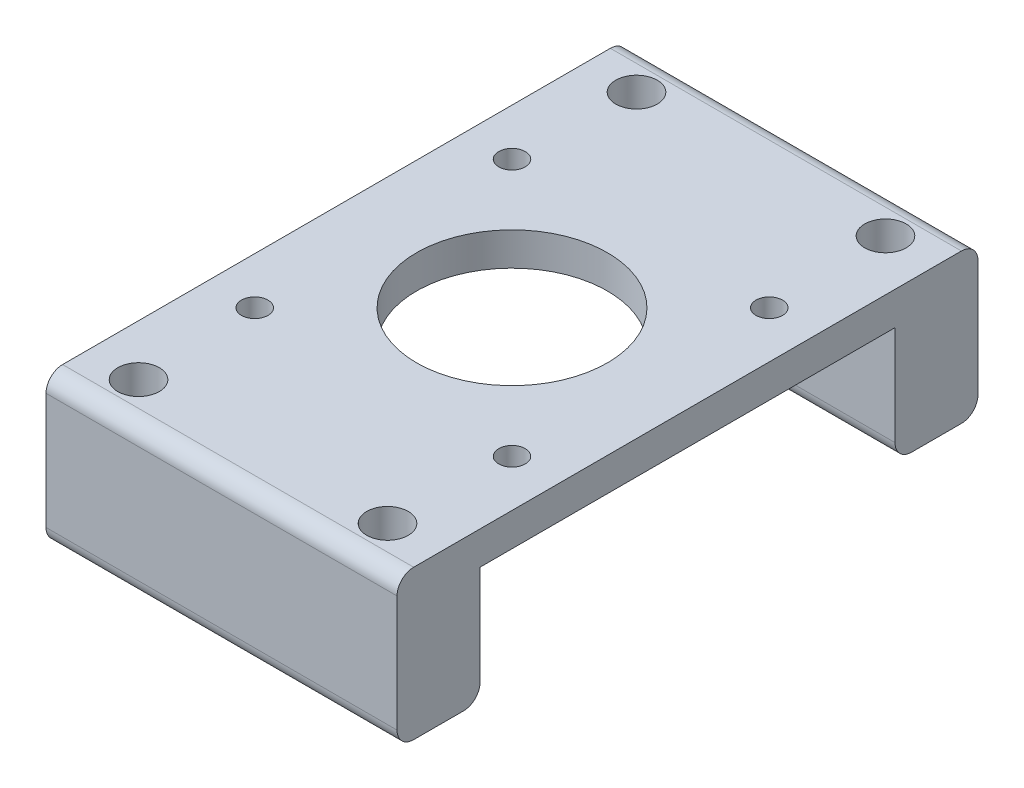
SolidWorks part; units mm, degrees
material "ABS"
ref_plane "Plano frontal" through (0, 0, 0) normal (0, 0, 1) x (1, 0, 0)
ref_plane "Plano superior" through (0, 0, 0) normal (0, 1, 0) x (1, 0, 0)
ref_plane "Plano direito" through (0, 0, 0) normal (1, 0, 0) x (0, 0, -1)
sketch "Esboço1" plane through (0, 0, 0) normal (1, 0, 0) x (0, 0, -1)
  line L1 (-25, 2) -> (25, 2)
  line L2 (-25, 2) -> (-25, -2)
  line L3 (-25, -2) -> (25, -2)
  line L4 (25, 2) -> (25, -2)
  line L5 (-25, 2) -> (25, -2) construction
  line L6 (-25, -2) -> (25, 2) construction
  line L7 (25, 2) -> (35, 2)
  line L8 (25, 2) -> (25, -16)
  line L9 (25, -16) -> (35, -16)
  line L10 (35, 2) -> (35, -16)
  line L11 (-25, 2) -> (-35, 2)
  line L12 (-25, 2) -> (-25, -16)
  line L13 (-25, -16) -> (-35, -16)
  line L14 (-35, 2) -> (-35, -16)
  point P0 (0, 0)
  dimension "D1" = 50
  dimension "D2" = 4
  dimension "D3" = 10
  dimension "D4" = 10
  dimension "D5" = 18
  dimension "D6" = 18
extrude "Ressalto-extrusão1" add sketch "Esboço1" along normal mid plane 42.3 contours L11 L14 L13 L12 L2 | L4 L1 L2 L3 | L10 L7 L4 L8 L9
sketch "Esboço3" plane through (0, 2, 0) normal (0, 1, 0) x (1, 0, 0)
  circle A0 centre (0, 0) radius 11.5
  dimension "D1" = 23
extrude "Corte-extrusão1" cut sketch "Esboço3" against normal through all
sketch "Esboço4" plane through (0, 2, 0) normal (0, 1, 0) x (1, 0, 0)
  circle A0 centre (-15.5, 15.5) radius 1.6
  dimension "D1" = 3.2
  dimension "D2" = 15.5
  dimension "D3" = 15.5
extrude "Corte-extrusão2" cut sketch "Esboço4" against normal through all
pattern_circular "PadrãoCircular1" count 4 over 360 about axis through (0, 0, 0) along (0, 1, 0) of "Corte-extrusão2"
sketch "Esboço5" plane through (0, -16, 0) normal (0, -1, 0) x (1, 0, 0)
  line L0 (21.15, -30) -> (-21.15, -30) construction
  line L1 (21.15, -25) -> (21.15, -35) construction
  line L2 (-21.15, -25) -> (-21.15, -35) construction
  line L3 (21.15, -25) -> (-21.15, -25) construction
  circle A0 centre (15, -30) radius 2.5
  point P8 (0, -25)
  dimension "D1" = 5
  dimension "D2" = 15
extrude "Corte-extrusão3" cut sketch "Esboço5" against normal through all
mirror "Espelhar1" about plane through (0, 0, 0) normal (1, 0, 0) of "Corte-extrusão3"
mirror "Espelhar2" about plane through (0, 0, 0) normal (0, 0, 1) of "Espelhar1", "Corte-extrusão3"
fillet "Filete1" radius 2 6 edges at (0, -16, 35) (0, -16, 25) (0, -16, -35) (0, -16, -25) (0, 2, 35) (0, 2, -35)
